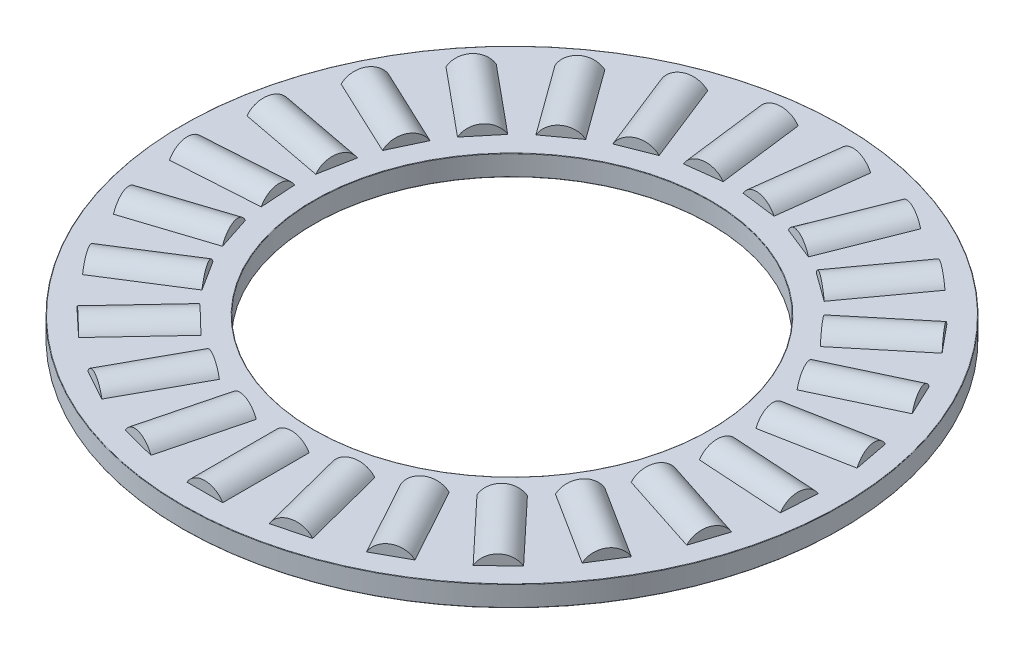
SolidWorks part; units mm, degrees
ref_plane "Front Plane" through (0, 0, 0) normal (0, 0, 1) x (1, 0, 0)
ref_plane "Top Plane" through (0, 0, 0) normal (0, 1, 0) x (1, 0, 0)
ref_plane "Right Plane" through (0, 0, 0) normal (1, 0, 0) x (0, 0, -1)
sketch "Sketch1" plane through (0, 0, 0) normal (1, 0, 0) x (0, 0, -1)
  line L0 (-15.875, 0) -> (15.875, 0) construction
  line L1 (0, -0.9922) -> (0, 0.9922) construction
  line L2 (-15.875, 0.4961) -> (-9.5504, 0.4961)
  line L3 (-15.875, 0.4961) -> (-15.875, -0.4961)
  line L4 (-15.875, -0.4961) -> (-9.5504, -0.4961)
  line L5 (-9.5504, 0.4961) -> (-9.5504, -0.4961)
  line L7 (-12.7127, 0.9922) -> (-12.7127, 0.4961) construction
  line L8 (-14.7963, 0.9922) -> (-10.6291, 0.9922) construction
  line L9 (-14.7963, 0.9922) -> (-14.7963, -0.9922) construction
  line L10 (-14.7963, -0.9922) -> (-10.6291, -0.9922) construction
  line L11 (-10.6291, 0.9922) -> (-10.6291, -0.9922) construction
  point P16 (-14.7963, 0)
  dimension "D1" = 4.1672
  dimension "OD" = 31.75
  dimension "Shaft Dia" = 19.1008
  dimension "Th" = 1.9844
  dimension "D2" = 0.9922
  dimension "D3" = 6.3246
revolve "Revolve1" add sketch "Sketch1" angle 360 about L1
sketch "Sketch3" plane through (0, 0, 0) normal (1, 0, 0) x (0, 0, -1)
  line L0 (-14.7963, 0.9922) -> (-14.7963, -0.9922) construction
  line L1 (-14.7963, 0) -> (-10.6291, 0)
  line L2 (-14.7963, 0) -> (-14.7963, 0.9922)
  line L3 (-14.7963, 0.9922) -> (-10.6291, 0.9922)
  line L4 (-10.6291, 0) -> (-10.6291, 0.9922)
revolve "Cut-Revolve1" cut sketch "Sketch3" angle 360 about L1
sketch "Sketch2" plane through (0, 0, 0) normal (1, 0, 0) x (0, 0, -1)
  line L1 (-14.7963, 0) -> (-10.6291, 0)
  line L2 (-14.7963, 0) -> (-14.7963, 0.9922)
  line L3 (-14.7963, 0.9922) -> (-10.6291, 0.9922)
  line L4 (-10.6291, 0) -> (-10.6291, 0.9922)
revolve "Revolve2" add sketch "Sketch2" angle 360 about L1
ref_axis "Axis1" through (0, 0.9922, 0) along (0, -1, 0)
pattern_circular "CirPattern1" count 25 every 14.4 about axis through (0, 0.9922, 0) along (0, -1, 0) of bodies 187 411
pattern_circular "CirPattern2" count 25 every 14.4 about axis through (0, 0, 0) along (0, 1, 0) of "Cut-Revolve1"
sketch "Sketch4" plane through (0, 0, 0) normal (1, 0, 0) x (0, 0, -1)
  line L0 (-15.875, 0.4961) -> (-15.875, -0.4961) construction
  line L1 (-11.9062, 9.1091) -> (-6.35, 9.1091)
  line L2 (-11.9062, 9.1091) -> (-11.9062, 9.9219)
  line L3 (-11.9062, 9.9219) -> (-6.35, 9.9219)
  line L4 (-6.35, 9.1091) -> (-6.35, 9.9219)
  line L5 (-11.9062, -9.9219) -> (-9.5504, -9.9219)
  line L6 (-11.9062, -9.9219) -> (-11.9062, -9.1091)
  line L7 (-11.9062, -9.1091) -> (-9.5504, -9.1091)
  line L8 (-9.5504, -9.9219) -> (-9.5504, -9.1091)
  line L10 (-9.5504, 0.4961) -> (-9.5504, -0.4961) construction
  line L11 (0, 0) -> (-15.875, 0) construction
  line L12 (-15.875, 0) -> (15.875, 0) construction
  line L13 (0, -0.9922) -> (0, 0.9922) construction
  dimension "Ht" = 19.8438
  dimension "Washer Th" = 0.8128
  dimension "Washer ID" = 12.7
  dimension "Washer OD" = 23.8125
fillet "Fillet2" radius 0.0198 4 edges at (0, -0.4961, -9.5504) (0, 0.4961, -9.5504) (0, -0.4961, -15.875) (0, 0.4961, -15.875)
equation "\"D2@Sketch1\"= \"Th@Sketch1\" * .5"
equation "\"Rollers@CirPattern1\"= \"OD@Sketch1\" * 20"
equation "\"Angle@CirPattern1\" = 360/\"Rollers@CirPattern1\""
equation "\"D1@CirPattern2\" = \"Rollers@CirPattern1\""
equation "\"D2@CirPattern2\" = \"Angle@CirPattern1\""
equation "\"Ht@Sketch4\" = \"Th@Sketch1\"*10"
